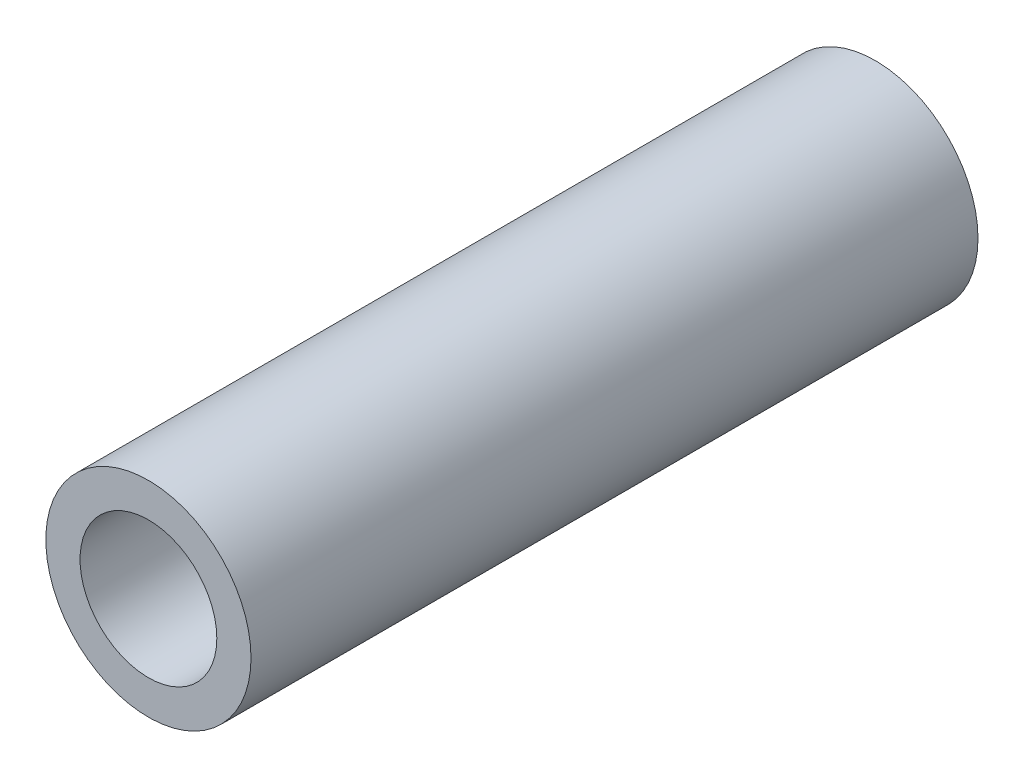
SolidWorks part; units mm, degrees
ref_plane "Płaszczyzna przednia" through (0, 0, 0) normal (0, 0, 1) x (1, 0, 0)
ref_plane "Płaszczyzna górna" through (0, 0, 0) normal (0, 1, 0) x (1, 0, 0)
ref_plane "Płaszczyzna prawa" through (0, 0, 0) normal (1, 0, 0) x (0, 0, -1)
sketch "Szkic1" plane through (0, 0, 0) normal (0, 0, 1) x (1, 0, 0)
  circle A0 centre (0, 0) radius 10
  circle A1 centre (0, 0) radius 15
  dimension "D1" = 20
  dimension "D2" = 30
extrude "Dodanie-wyciągnięcie1" add sketch "Szkic1" along normal mid plane 106.3
